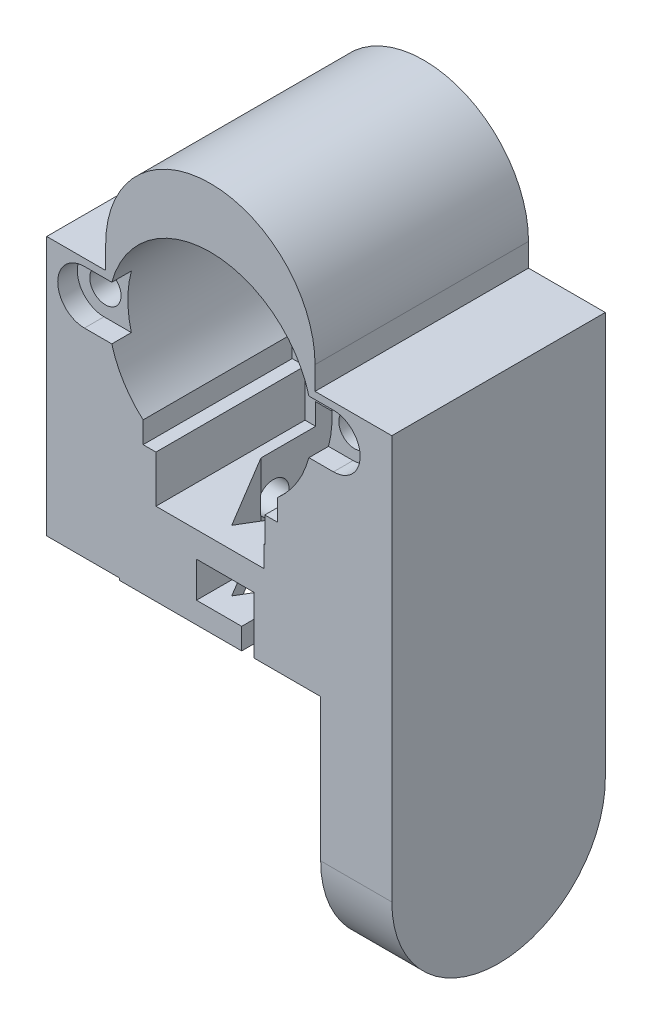
SolidWorks part; units mm, degrees
ref_plane "Front Plane" through (0, 0, 0) normal (0, 0, 1) x (1, 0, 0)
ref_plane "Top Plane" through (0, 0, 0) normal (0, 1, 0) x (1, 0, 0)
ref_plane "Right Plane" through (0, 0, 0) normal (1, 0, 0) x (0, 0, -1)
sketch "Sketch2" plane through (0, 0, 0) normal (0, 0, 1) x (1, 0, 0)
  line L0 (-7.65, 18.1811) -> (-7.65, 14.59)
  line L1 (-7.65, 14.59) -> (7.65, 14.59)
  line L2 (7.65, 14.59) -> (7.65, 18.1811)
  line L3 (7.65, 18.1811) -> (9.45, 18.1811)
  line L4 (9.45, 18.1811) -> (9.45, 21.2003)
  line L5 (-7.65, 18.1811) -> (-9.45, 18.1811)
  line L6 (-9.45, 18.1811) -> (-9.45, 21.2003)
  line L7 (-14.7095, 40) -> (-23, 40)
  line L8 (-23, 40) -> (-23, 0)
  line L10 (14.7095, 40) -> (23, 40)
  line L11 (23, 40) -> (23, 0)
  line L13 (-23, 0) -> (23, 0)
  arc A0 (14.7095, 40) -> (-14.7095, 40) centre (0, 40) ccw
  arc A4 (9.45, 21.2003) -> (-9.45, 21.2003) centre (0, 31.9993) ccw
  point P6 (0, 14.59)
  point P15 (0, 0)
  dimension "D1" = 8.2905
  dimension "D12" = 3.5911
  dimension "D16" = 14.35
  dimension "D17" = 14.7095
  dimension "D2" = 8.2905
  dimension "D3" = 25.41
  dimension "D4" = 40
  dimension "D5" = 0
  dimension "D6" = 0
  dimension "D7" = 46
  dimension "D9" = 3.0191
  dimension "D10" = 1.8
  dimension "D11" = 1.8
  dimension "D13" = 15.3
  dimension "D14" = 3.0191
  dimension "D15" = 3.5911
extrude "Boss-Extrude1" add sketch "Sketch2" along normal blind 20.95
sketch "Sketch3" plane through (0, 0, 0) normal (0, 0, 1) x (1, 0, 0)
  line L7 (-14.7095, 40) -> (-23, 40)
  line L8 (-23, 40) -> (-23, 0)
  line L9 (14.7095, 40) -> (23, 40)
  line L10 (23, 40) -> (23, 0)
  line L11 (-23, 0) -> (23, 0)
  line L12 (23, 40) -> (14.7095, 40) construction
  line L13 (-23, 40) -> (-23, 0) construction
  line L17 (-23, 0) -> (23, 0) construction
  line L19 (23, 0) -> (23, 40) construction
  arc A0 (14.7095, 40) -> (-14.7095, 40) centre (0, 40) ccw
  arc A1 (14.7095, 40) -> (-14.7095, 40) centre (0, 40) ccw construction
  dimension "D1" = 0
extrude "Boss-Extrude2" add sketch "Sketch3" against normal blind 9.05
sketch "Sketch6" plane through (0, 0, 20.95) normal (0, 0, 1) x (1, 0, 0)
  line L0 (-14.7095, 40) -> (-23, 40) construction
  line L1 (-23, 40) -> (-23, 0) construction
  line L2 (23, 40) -> (14.7095, 40) construction
  line L3 (23, 0) -> (23, 40) construction
  circle A0 centre (-17.5, 32) radius 2.2
  circle A1 centre (17.5, 32) radius 2.2
  dimension "D1" = 8
  dimension "D2" = 5.5
  dimension "D3" = 4.4
  dimension "D4" = 8
  dimension "D5" = 5.5
  dimension "D6" = 4.4
extrude "Cut-Extrude2" cut sketch "Sketch6" against normal blind 10
sketch "Sketch7" plane through (0, 0, 20.95) normal (0, 0, 1) x (1, 0, 0)
  line L0 (-17.7, 32) -> (17.3, 32) construction
  line L3 (-17.7, 35.75) -> (17.3, 35.75)
  line L4 (-17.7, 28.25) -> (17.3, 28.25)
  arc A2 (-17.7, 35.75) -> (-17.7, 28.25) centre (-17.7, 32) ccw
  arc A3 (17.3, 28.25) -> (17.3, 35.75) centre (17.3, 32) ccw
  circle A4 centre (-17.5, 32) radius 2.2 construction
  circle A5 centre (-17.5, 32) radius 2.2 construction
  circle A6 centre (17.5, 32) radius 2.2 construction
  point P2 (-0.2, 32)
  dimension "D2" = 7.5
  dimension "D3" = 1.75
  dimension "D4" = 1.75
  dimension "D1" = 3.75
extrude "Cut-Extrude3" cut sketch "Sketch7" against normal blind 2.75
sketch "Sketch8" plane through (0, 0, 20.95) normal (0, 0, 1) x (1, 0, 0)
  line L0 (-14.7095, 40) -> (-23, 40) construction
  line L1 (-14.7095, 40) -> (-23, 40)
  line L2 (-14.7095, 40) -> (-14.7095, 36.75)
  line L3 (-14.7095, 36.75) -> (-23, 36.75)
  line L4 (-23, 40) -> (-23, 36.75)
  line L5 (14.7095, 40) -> (23, 40)
  line L6 (14.7095, 40) -> (14.7095, 36.75)
  line L7 (14.7095, 36.75) -> (23, 36.75)
  line L8 (23, 40) -> (23, 36.75)
  line L9 (-23, 40) -> (-23, 0) construction
  line L10 (-13.8512, 35.75) -> (-17.7, 35.75) construction
  line L11 (17.3, 35.75) -> (13.8512, 35.75) construction
  line L12 (23, 0) -> (23, 40) construction
  line L13 (23, 40) -> (14.7095, 40) construction
  dimension "D2" = 1
  dimension "D3" = 1
extrude "Cut-Extrude4" cut sketch "Sketch8" along normal through all both and the other way through all
sketch "Sketch11" plane through (0, 0, -9.05) normal (0, 0, -1) x (-1, 0, 0)
  circle A0 centre (0, 40) radius 11.25
  arc A1 (14.7095, 40) -> (-14.7095, 40) centre (0, 40) ccw construction
  dimension "D1" = 22.5
extrude "Bearing Hole" cut sketch "Sketch11" against normal blind 7.6
sketch "Sketch9" plane through (0, 14.59, -19.25) normal (0, 1, 0) x (-1, 0, 0)
  line L0 (7.65, 40.2) -> (-7.65, 40.2) construction
  line L1 (-6.15, 37.7) -> (6.15, 37.7)
  line L2 (-6.15, 37.7) -> (-6.15, 16.2)
  line L3 (-6.15, 16.2) -> (6.15, 16.2)
  line L4 (6.15, 37.7) -> (6.15, 16.2)
  line L8 (-7.65, 40.2) -> (-7.65, 19.25) construction
  line L9 (7.65, 40.2) -> (7.65, 19.25) construction
  line L10 (7.65, 10.2) -> (-7.65, 10.2) construction
  dimension "D1" = 2.5
  dimension "D2" = 1.5
  dimension "D3" = 1.5
  dimension "D4" = 6
extrude "Wire Hole" cut sketch "Sketch9" against normal through all
sketch "Sketch12" plane through (0, 0, 0) normal (0, -1, 0) x (1, 0, 0)
  line L0 (-23, -9.05) -> (23, -9.05) construction
  line L1 (-23, -9.05) -> (23, -9.05)
  line L2 (-23, -9.05) -> (-23, 20.95)
  line L3 (-23, 20.95) -> (23, 20.95)
  line L4 (23, -9.05) -> (23, 20.95)
  line L5 (-23, 20.95) -> (23, 20.95) construction
  line L7 (-23, 20.95) -> (-23, -9.05) construction
  point P4 (0, -9.05)
  dimension "D1" = 0
  dimension "D2" = 0
  dimension "D3" = 0
  dimension "D4" = 0
extrude "Boss-Extrude3" add sketch "Sketch12" along normal blind 0.0001
sketch "Sketch13" plane through (23, 0, 0) normal (1, 0, 0) x (0, 0, -1)
  line L0 (-20.95, -0.0001) -> (-20.95, -20.0001)
  line L1 (9.05, -0.0001) -> (9.05, -20.0001)
  line L6 (9.05, 36.75) -> (-20.95, 36.75)
  line L7 (-20.95, 36.75) -> (-20.95, -0.0001)
  line L8 (-20.95, -0.0001) -> (9.05, -0.0001)
  line L9 (9.05, -0.0001) -> (9.05, 36.75)
  line L12 (-20.95, -0.0001) -> (9.05, -0.0001)
  arc A0 (-20.95, -20.0001) -> (9.05, -20.0001) centre (-5.95, -20.0001) ccw
  dimension "D1" = 0
  dimension "D2" = 20
extrude "Boss-Extrude4" add sketch "Sketch13" against normal blind 7.5
sketch "Sketch14" plane through (-23, 0, 0) normal (-1, 0, 0) x (0, 0, 1)
  line L0 (-9.05, -20.0001) -> (-9.05, -0.0001)
  line L1 (-9.05, -0.0001) -> (20.95, -0.0001)
  line L2 (20.95, -0.0001) -> (20.95, -20.0001)
  arc A0 (-9.05, -20.0001) -> (20.95, -20.0001) centre (5.95, -20.0001) ccw
extrude "Boss-Extrude5" add sketch "Sketch14" against normal blind 7.5
sketch "Sketch21" plane through (23, 0, 0) normal (1, 0, 0) x (0, 0, -1)
  line L0 (-20.95, -20.0001) -> (-20.95, 36.75)
  line L1 (-20.95, 36.75) -> (9.05, 36.75)
  line L2 (9.05, 36.75) -> (9.05, -20.0001)
  arc A0 (-20.95, -20.0001) -> (9.05, -20.0001) centre (-5.95, -20.0001) ccw
extrude "Boss-Extrude9" add sketch "Sketch21" along normal blind 2.5
sketch "Sketch15" plane through (-23, 0, 0) normal (-1, 0, 0) x (0, 0, 1)
  circle A0 centre (5.95, -20.0001) radius 4
extrude "Cut-Extrude5" cut sketch "Sketch15" against normal through all
sketch "Sketch17" plane through (25.5, 0, -23) normal (-1, 0, 0) x (0, 0, 1)
  line L4 (26.8764, -18.3501) -> (31.0236, -18.3501)
  line L5 (26.8764, -21.6501) -> (31.0236, -21.6501)
  arc A10 (26.8764, -18.3501) -> (26.8764, -21.6501) centre (28.95, -20.0001) ccw
  arc A11 (31.0236, -18.3501) -> (31.0236, -21.6501) centre (28.95, -20.0001) cw
  circle A14 centre (28.95, -20.0001) radius 6.1696
  arc A16 (13.95, -20.0001) -> (43.95, -20.0001) centre (28.95, -20.0001) ccw construction
  circle A17 centre (28.95, -20.0001) radius 4 construction
  point P11 (28.95, -35.0001)
  dimension "D1" = 3.3
  dimension "D2" = 1.65
  dimension "D3" = 2.65
  dimension "D4" = 2.65
extrude "Shat hole" add sketch "Sketch17" along normal up to surface (10 mm away) up to face at (15.5, -20.0001, 1.95)
sketch "Sketch18" plane through (-23, 0, 0) normal (-1, 0, 0) x (0, 0, 1)
  circle A0 centre (5.95, -20.0001) radius 4
  dimension "D1" = 8
extrude "Boss-Extrude7" add sketch "Sketch18" against normal offset from surface (14 mm away) 6.5 up to face at (-15.5, -24.0001, 5.95) offset beyond the face yes
sketch "Sketch19" plane through (15.5, 0, 0) normal (-1, 0, 0) x (0, 0, 1)
  circle A0 centre (5.95, -20.0001) radius 4.675
  dimension "D1" = 9.35
extrude "Cut-Extrude6" cut sketch "Sketch19" against normal blind 2
sketch "Sketch24" plane through (0, 0, -1.45) normal (0, 0, -1) x (-1, 0, 0)
  circle A0 centre (0, 40) radius 5
  dimension "D1" = 10
extrude "Cut-Extrude7" cut sketch "Sketch24" against normal through all
fillet "Fillet1" radius 1 1 edges at (-11.25, 40, -9.05)
sketch "Sketch25" plane through (25.5, 0, 0) normal (1, 0, 0) x (0, 0, -1)
  line L1 (-10.6075, -17.9723) -> (-1.7642, -17.9723)
  line L2 (-10.6075, -17.9723) -> (-10.6075, -22.8066)
  line L3 (-10.6075, -22.8066) -> (-1.7642, -22.8066)
  line L4 (-1.7642, -17.9723) -> (-1.7642, -22.8066)
extrude "Boss-Extrude10" add sketch "Sketch25" against normal blind 2
sketch "Sketch27" plane through (0, 14.59, 0) normal (0, 1, 0) x (1, 0, 0)
  line L1 (-6.15, -18.45) -> (6.15, -18.45)
  line L2 (-6.15, -18.45) -> (-6.15, 3.05)
  line L3 (-6.15, 3.05) -> (6.15, 3.05)
  line L4 (6.15, -18.45) -> (6.15, 3.05)
extrude "Cut-Extrude8" cut sketch "Sketch27" against normal through all
sketch "Sketch28" plane through (0, -0.0001, 0) normal (0, -1, 0) x (1, 0, 0)
  line L1 (-6.15, -3.05) -> (-6.15, 18.45) construction
  line L2 (6.15, 18.45) -> (6.15, -3.05) construction
  line L4 (-6.15, 7.7) -> (0, 17.95)
  line L5 (0, 17.95) -> (6.15, 7.7)
  line L8 (-6.15, -3.05) -> (6.15, -3.05)
  line L9 (-6.15, 18.45) -> (-6.15, -3.05)
  line L10 (6.15, 18.45) -> (-6.15, 18.45)
  line L11 (6.15, -3.05) -> (6.15, 18.45)
  line L13 (-6.15, 18.45) -> (-6.15, 7.7)
  line L14 (6.15, 18.45) -> (-6.15, 18.45)
  line L15 (6.15, 7.7) -> (6.15, 18.45)
  dimension "D1" = 0
  dimension "D2" = 0.5
extrude "Boss-Extrude11" add sketch "Sketch28" against normal up to surface (14.5901 mm away) up to face at (0, 14.59, 9.85)
sketch "Sketch29" plane through (0, 0, 20.95) normal (0, 0, 1) x (1, 0, 0)
  line L1 (-7.65, 14.59) -> (7.55, 14.59)
  line L2 (-7.65, 14.59) -> (-7.65, 11.59)
  line L3 (-7.65, 11.59) -> (7.55, 11.59)
  line L4 (7.55, 14.59) -> (7.55, 11.59)
  dimension "D1" = 3
extrude "Cut-Extrude9" cut sketch "Sketch29" against normal up to surface (20.95 mm away) up to face at (5, 40, 0)
sketch "Sketch33" plane through (-23, 0, 0) normal (-1, 0, 0) x (0, 0, 1)
  line L0 (-4.35, 11.89) -> (16.25, 11.89)
  line L2 (16.25, 11.89) -> (11.25, 0.2999)
  line L3 (20.95, -0.0001) -> (-9.05, -0.0001) construction
  line L4 (11.25, 0.2999) -> (20.95, 0.2999)
  line L5 (20.95, 0.2999) -> (20.95, -20.0001)
  line L6 (-4.35, 11.89) -> (0.65, 0.2999)
  line L7 (0.65, 0.2999) -> (-9.05, 0.2999)
  line L8 (-9.05, 0.2999) -> (-9.05, -20.0001)
  line L9 (0, 11.59) -> (20.95, 11.59) construction
  arc A0 (-9.05, -20.0001) -> (20.95, -20.0001) centre (5.95, -20.0001) ccw
  point P17 (5.95, -0.0001)
  point P24 (5.95, 11.89)
  dimension "D1" = 20.6
  dimension "D2" = 10.6
  dimension "D3" = 5.3
  dimension "D4" = 0.3
  dimension "D5" = 0.3
  dimension "D6" = 0
extrude "Cut-Extrude14" cut sketch "Sketch33" against normal blind 10.25
sketch "Sketch34" plane through (-12.75, 0, 0) normal (-1, 0, 0) x (0, 0, 1)
  circle A0 centre (5.95, -20.0001) radius 6.9014
extrude "Cut-Extrude15" cut sketch "Sketch34" against normal blind 5
fillet "Fillet2" radius 0.5 2 edges at (-17.875, 0.2999, 11.25) (-17.875, 0.2999, 0.65)
sketch "Sketch35" plane through (-12.75, 0, 0) normal (-1, 0, 0) x (0, 0, 1)
  line L1 (16.25, 11.89) -> (-4.35, 11.89) construction
  circle A0 centre (5.95, 5.89) radius 2.2
  point P7 (5.95, 11.89)
  dimension "D1" = 0
  dimension "D3" = 4.4
  dimension "D2" = 6
extrude "Cut-Extrude16" cut sketch "Sketch35" against normal blind 6.7
sketch "Sketch36" plane through (-23, 0, 0) normal (-1, 0, 0) x (0, 0, 1)
  line L0 (16.25, 11.89) -> (-4.35, 11.89) construction
  line L1 (11.5511, 0.998) -> (16.25, 11.89) construction
  line L2 (-4.35, 11.89) -> (0.3489, 0.998) construction
  line L3 (-3.9539, 10.9718) -> (-4.35, 11.89)
  line L4 (-4.35, 11.89) -> (-3.35, 11.89)
  line L5 (15.8539, 10.9718) -> (16.25, 11.89)
  line L6 (16.25, 11.89) -> (15.25, 11.89)
  arc A0 (15.25, 11.89) -> (15.8539, 10.9718) centre (16.25, 11.89) cw
  arc A1 (-3.35, 11.89) -> (-3.9539, 10.9718) centre (-4.35, 11.89) ccw
  dimension "D1" = 1
extrude "Cut-Extrude17" cut sketch "Sketch36" against normal up to surface (10.25 mm away) up to face at (-12.75, 3.69, 5.95)
sketch "Sketch37" plane through (0, 0, 20.95) normal (0, 0, 1) x (1, 0, 0)
  line L0 (6.15, -0.0001) -> (6.15, 7.9999)
  line L2 (6.15, 11.59) -> (6.15, -0.0001) construction
  line L3 (6.15, 7.9999) -> (-1.95, 7.9999)
  line L4 (-1.95, 7.9999) -> (-1.95, 2.9999)
  line L5 (-1.95, 2.9999) -> (4.4, 2.9999)
  line L6 (4.4, 2.9999) -> (4.4, -0.0001)
  line L7 (15.5, -0.0001) -> (-12.75, -0.0001) construction
  line L8 (4.4, -0.0001) -> (6.15, -0.0001)
  dimension "D1" = 1.75
  dimension "D2" = 8.1
  dimension "D3" = 5
  dimension "D4" = 3
extrude "Cut-Extrude18" cut sketch "Sketch37" against normal up to next
